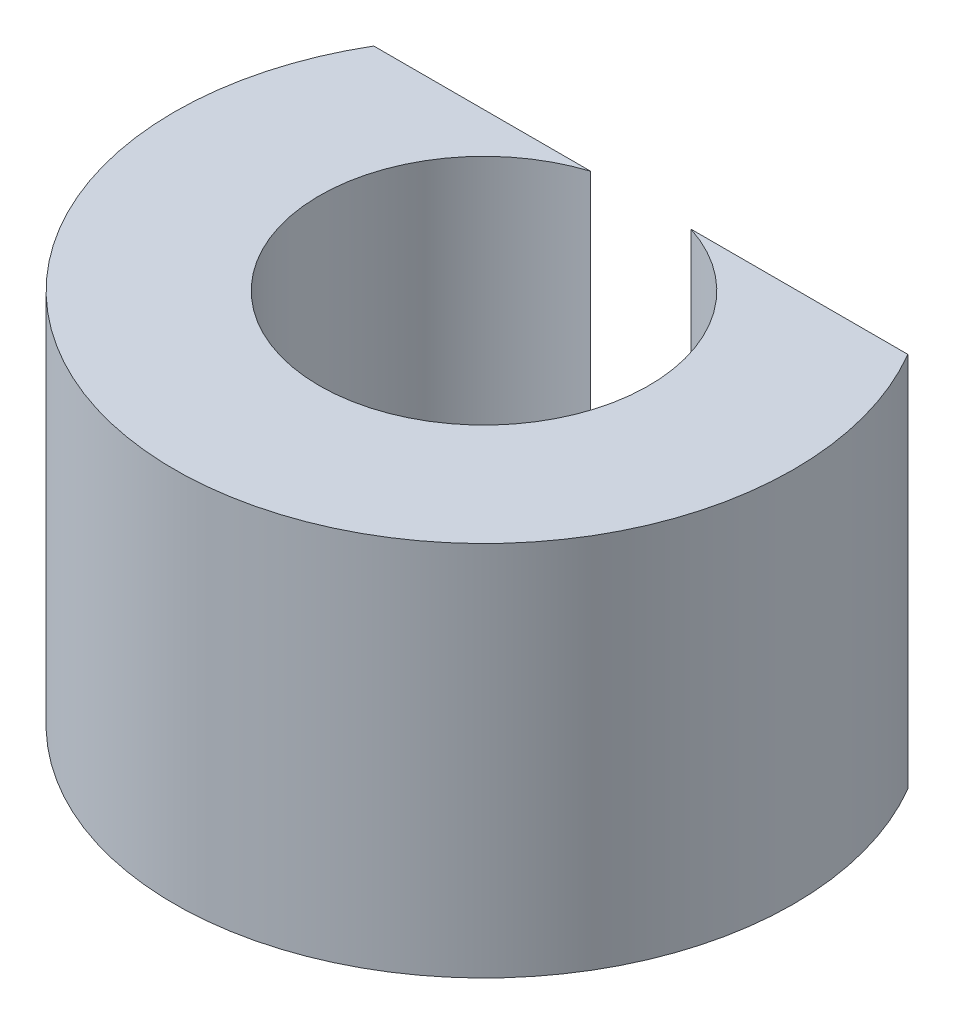
SolidWorks part; units mm, degrees
ref_plane "Front Plane" through (0, 0, 0) normal (0, 0, 1) x (1, 0, 0)
ref_plane "Top Plane" through (0, 0, 0) normal (0, 1, 0) x (1, 0, 0)
ref_plane "Right Plane" through (0, 0, 0) normal (1, 0, 0) x (0, 0, -1)
sketch "Sketch1" plane through (0, 0, 0) normal (0, 1, 0) x (1, 0, 0)
  line L0 (-1.7031, 1) -> (1.7031, 1)
  circle A0 centre (0, 0) radius 1.975
  dimension "D1" = 3.95
  dimension "D3" = 1
extrude "Boss-Extrude1" add sketch "Sketch1" along normal blind 2.4 contours L0 A0
sketch "Sketch2" plane through (0, 2.4, 0) normal (0, 1, 0) x (1, 0, 0)
  circle A0 centre (0, 0) radius 1.05
  dimension "D1" = 2.1
extrude "Cut-Extrude1" cut sketch "Sketch2" against normal through all
